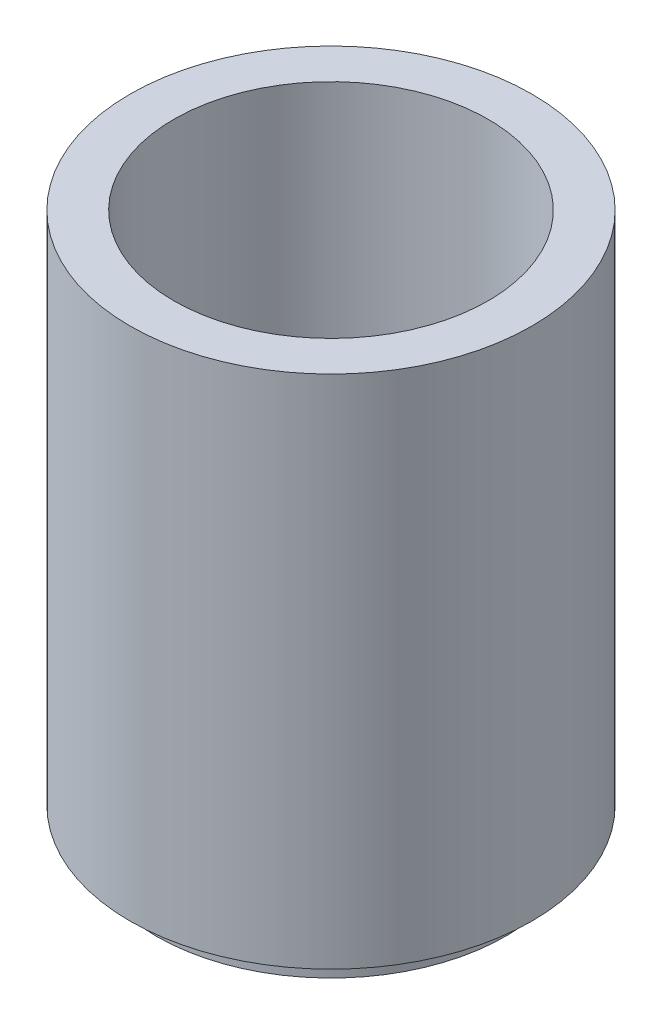
SolidWorks part; units mm, degrees
material "AISI 1015 Steel, Cold Drawn (SS)"
ref_plane "Front Plane" through (0, 0, 0) normal (0, 0, 1) x (1, 0, 0)
ref_plane "Top Plane" through (0, 0, 0) normal (0, 1, 0) x (1, 0, 0)
ref_plane "Right Plane" through (0, 0, 0) normal (1, 0, 0) x (0, 0, -1)
sketch "Sketch2" plane through (0, 0, 0) normal (0, 0, 1) x (1, 0, 0)
  line L0 (0, 34) -> (0, -32.7059) construction
  line L1 (9, -23) -> (9, 0)
  line L2 (9, 0) -> (11.5, 0)
  line L3 (11.5, 0) -> (11.5, -29.5)
  line L4 (11.5, -29.5) -> (10, -29.5)
  line L5 (10, -29.5) -> (10, -31)
  line L6 (10, -31) -> (8, -31)
  line L7 (8, -31) -> (8, -23)
  line L8 (8, -23) -> (9, -23)
  dimension "D1" = 9
  dimension "D2" = 11.5
  dimension "D3" = 1.5
  dimension "D4" = 1.5
  dimension "D5" = 8
  dimension "D6" = 8
  dimension "D7" = 23
revolve "Revolve1" add sketch "Sketch2" angle 360 about L0
cosmetic thread "Cosmetic Thread1"
